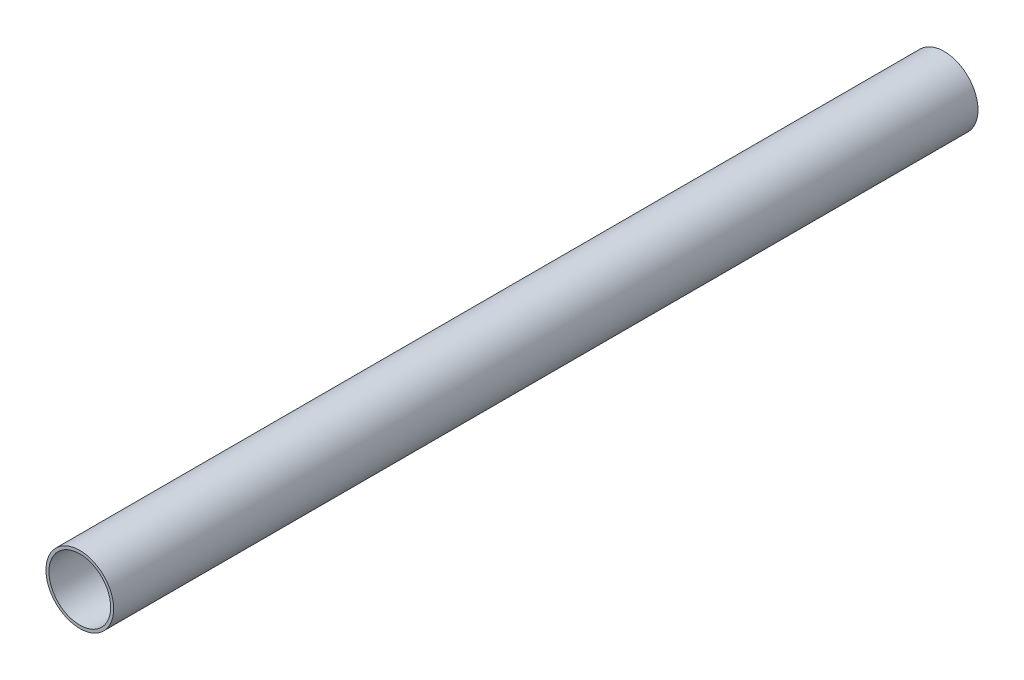
SolidWorks part; units mm, degrees
material "Silicon Rubber"
ref_plane "Front Plane" through (0, 0, 0) normal (0, 0, 1) x (1, 0, 0)
ref_plane "Top Plane" through (0, 0, 0) normal (0, 1, 0) x (1, 0, 0)
ref_plane "Right Plane" through (0, 0, 0) normal (1, 0, 0) x (0, 0, -1)
sketch "Sketch1" plane through (0, 0, 0) normal (0, 0, 1) x (1, 0, 0)
  circle A0 centre (0, 0) radius 13.9303
  circle A1 centre (0, 0) radius 12.7
  dimension "D1" = 27.8605
  dimension "D2" = 25.4
extrude "Boss-Extrude1" add sketch "Sketch1" along normal mid plane 355.6
equation "\"D1@Sketch1\"=sqr(0.875^2-0.75^2+1)"
